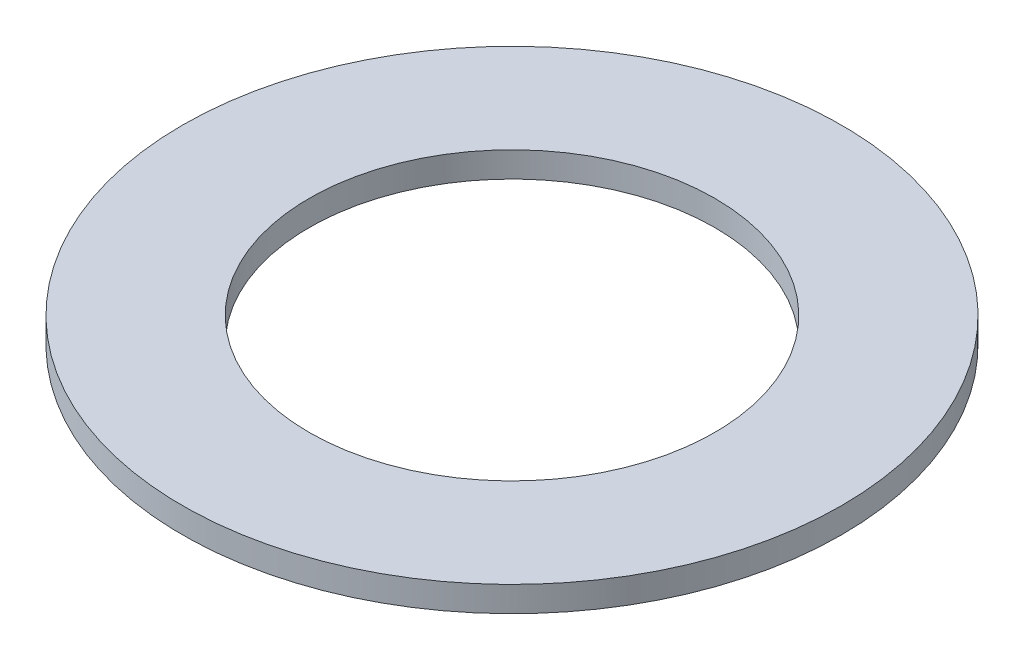
SolidWorks part; units mm, degrees
material "Plain Carbon Steel"
ref_plane "Front Plane" through (0, 0, 0) normal (0, 0, 1) x (1, 0, 0)
ref_plane "Top Plane" through (0, 0, 0) normal (0, 1, 0) x (1, 0, 0)
ref_plane "Right Plane" through (0, 0, 0) normal (1, 0, 0) x (0, 0, -1)
sketch "Sketch1" plane through (0, 0, 0) normal (0, 1, 0) x (1, 0, 0)
  circle A0 centre (0, 0) radius 8
  dimension "D1" = 16
extrude "Extrude-Thin1" add sketch "Sketch1" along normal blind 1 thin
